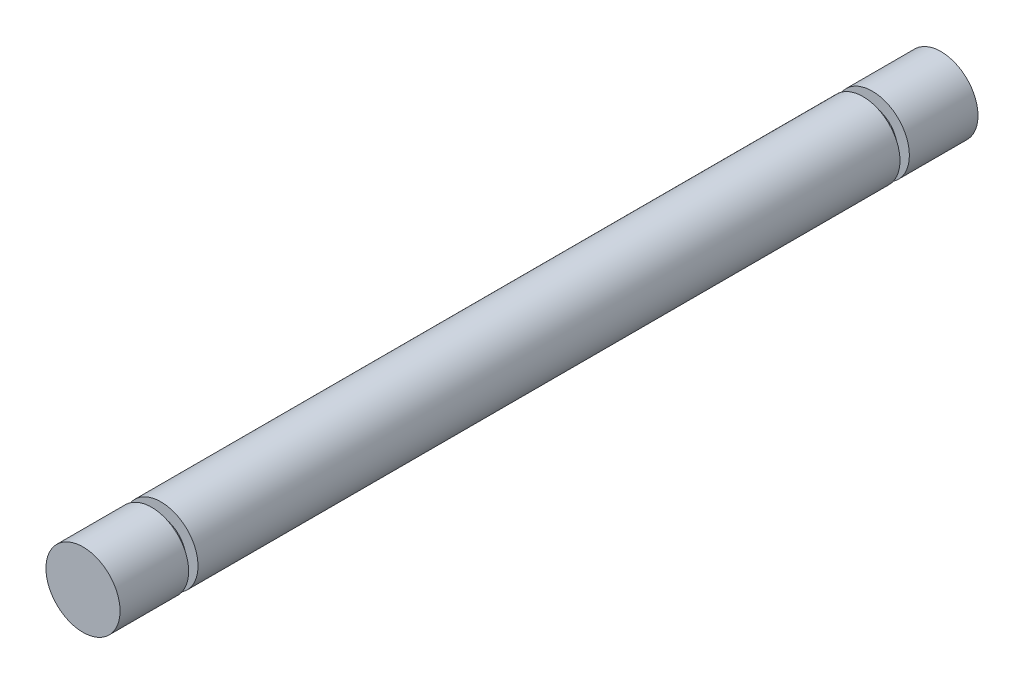
SolidWorks part; units mm, degrees
ref_plane "Front Plane" through (0, 0, 0) normal (0, 0, 1) x (1, 0, 0)
ref_plane "Top Plane" through (0, 0, 0) normal (0, 1, 0) x (1, 0, 0)
ref_plane "Right Plane" through (0, 0, 0) normal (1, 0, 0) x (0, 0, -1)
sketch "Sketch1" plane through (0, 0, 0) normal (0, 0, 1) x (1, 0, 0)
  circle A0 centre (0, 0) radius 2.375
  dimension "D1" = 4.75
extrude "Boss-Extrude1" add sketch "Sketch1" along normal blind 22.5 contours A0
sketch "Sketch2" plane through (0, 0, 22.5) normal (0, 0, 1) x (1, 0, 0)
  circle A0 centre (0, 0) radius 1.6
  dimension "D1" = 3.2
extrude "Boss-Extrude2" add sketch "Sketch2" along normal blind 0.6
sketch "Sketch3" plane through (0, 0, 23.1) normal (0, 0, 1) x (1, 0, 0)
  circle A0 centre (0, 0) radius 2.375
  dimension "D1" = 4.75
extrude "Boss-Extrude3" add sketch "Sketch3" along normal blind 4.4 contours A0
mirror "Mirror1" about plane through (0, 0, 0) normal (0, 0, 1) of "Boss-Extrude1", "Boss-Extrude2", "Boss-Extrude3"
